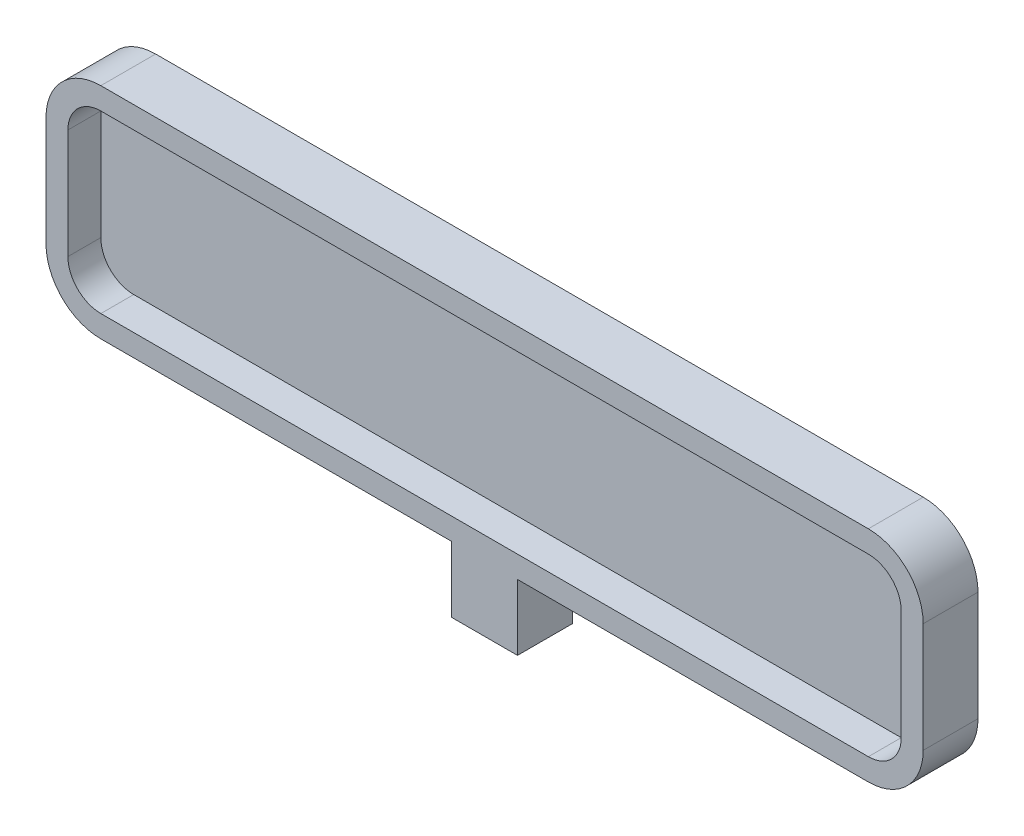
SolidWorks part; units mm, degrees
ref_plane "Front Plane" through (0, 0, 0) normal (0, 0, 1) x (1, 0, 0)
ref_plane "Top Plane" through (0, 0, 0) normal (0, 1, 0) x (1, 0, 0)
ref_plane "Right Plane" through (0, 0, 0) normal (1, 0, 0) x (0, 0, -1)
sketch "Sketch1" plane through (0, 0, 0) normal (0, 0, 1) x (1, 0, 0)
  line L1 (-40, -10) -> (40, -10)
  line L2 (-40, -10) -> (-40, 10)
  line L3 (-40, 10) -> (40, 10)
  line L4 (40, -10) -> (40, 10)
  line L5 (-40, -10) -> (40, 10) construction
  line L6 (-40, 10) -> (40, -10) construction
  point P0 (0, 0)
  dimension "D1" = 80
  dimension "D2" = 20
extrude "Boss-Extrude1" add sketch "Sketch1" along normal mid plane 5
fillet "Fillet1" radius 5 4 edges at (-40, -10, 0) (40, -10, 0) (40, 10, 0) (-40, 10, 0)
shell "Shell1" thickness 2
sketch "Sketch2" plane through (0, -10, 0) normal (0, -1, 0) x (1, 0, 0)
  line L0 (-35, 2.5) -> (35, 2.5) construction
  line L1 (-3, -2.5) -> (3, -2.5)
  line L2 (-3, -2.5) -> (-3, 2.5)
  line L3 (-3, 2.5) -> (3, 2.5)
  line L4 (3, -2.5) -> (3, 2.5)
  line L5 (-3, -2.5) -> (3, 2.5) construction
  line L6 (-3, 2.5) -> (3, -2.5) construction
  point P0 (0, 0)
  dimension "D1" = 6
extrude "Boss-Extrude2" add sketch "Sketch2" along normal blind 6
sketch "Sketch3" plane through (0, -16, 0) normal (0, -1, 0) x (1, 0, 0)
  circle A0 centre (0, 0) radius 1.425
  dimension "D1" = 2.85
extrude "Cut-Extrude1" cut sketch "Sketch3" against normal blind 4
